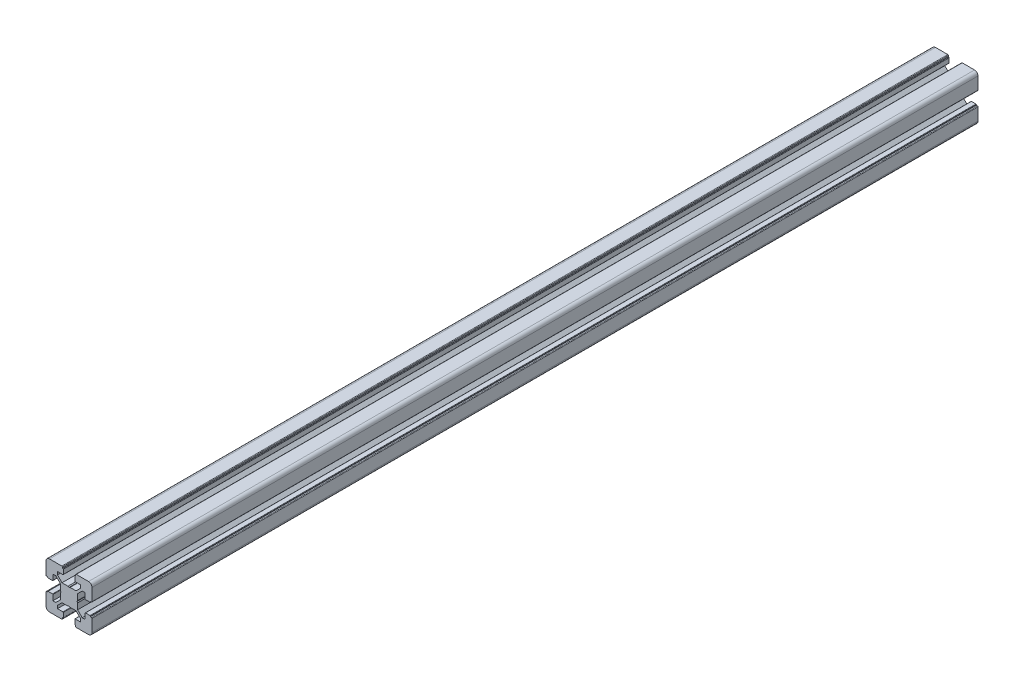
SolidWorks part; units mm, degrees
material "1060 Alloy"
ref_plane "Front Plane" through (0, 0, 0) normal (0, 0, 1) x (1, 0, 0)
ref_plane "Top Plane" through (0, 0, 0) normal (0, 1, 0) x (1, 0, 0)
ref_plane "Right Plane" through (0, 0, 0) normal (1, 0, 0) x (0, 0, -1)
sketch "Sketch2" plane through (0, 0, 0) normal (0, 0, 1) x (1, 0, 0)
  line L72 (-20.3, 9.9499) -> (-20.3, 14.7)
  line L73 (-20.6, 15) -> (-24.5, 15)
  line L74 (-24.8, 14.7) -> (-24.8, 14.2)
  line L75 (-24.8, 14.2) -> (-25.8, 14.2)
  line L76 (-26.3, 13.7) -> (-26.3, 3)
  line L77 (-23.3, 0) -> (-12.6, 0)
  line L78 (-12.1, 0.5) -> (-12.1, 1.5)
  line L79 (-12.1, 1.5) -> (-11.6, 1.5)
  line L80 (-11.3, 1.8) -> (-11.3, 5.7)
  line L81 (-11.6, 6) -> (-16.3501, 6)
  line L82 (-16.3501, 6) -> (-16.3501, 8.5356)
  line L83 (-16.3501, 8.5356) -> (-12.3856, 12.5001)
  line L84 (-12.3856, 12.5001) -> (-7.166, 12.5001)
  line L85 (-7.166, 12.5001) -> (-6.3, 13.0001)
  line L86 (-6.3, 13.0001) -> (-5.4339, 12.5001)
  line L87 (-5.4339, 12.5001) -> (-0.2143, 12.5001)
  line L88 (-0.2143, 12.5001) -> (3.7501, 8.5357)
  line L89 (3.7501, 8.5357) -> (3.7501, 6)
  line L90 (3.7501, 6) -> (-1, 6)
  line L91 (-1.3, 5.7) -> (-1.3, 1.8)
  line L92 (-1, 1.5) -> (-0.5, 1.5)
  line L93 (-0.5, 1.5) -> (-0.5, 0.5)
  line L94 (0, 0) -> (10.7, 0)
  line L95 (13.7, 3) -> (13.7, 13.7)
  line L96 (13.2, 14.2) -> (12.2, 14.2)
  line L97 (12.2, 14.2) -> (12.2, 14.7)
  line L98 (11.9, 15) -> (8, 15)
  line L99 (7.7, 14.7) -> (7.7, 9.9498)
  line L100 (7.7, 9.9498) -> (5.1644, 9.9498)
  line L101 (5.1644, 9.9498) -> (1.1999, 13.9143)
  line L102 (1.1999, 13.9143) -> (1.1999, 19.134)
  line L103 (1.1999, 19.134) -> (0.6999, 20)
  line L104 (0.6999, 20) -> (1.1999, 20.866)
  line L105 (1.1999, 20.866) -> (1.1999, 26.0857)
  line L106 (1.1999, 26.0857) -> (5.1643, 30.0501)
  line L107 (5.1643, 30.0501) -> (7.7, 30.0501)
  line L108 (7.7, 30.0501) -> (7.7, 25.3)
  line L109 (8, 25) -> (11.9, 25)
  line L110 (12.2, 25.3) -> (12.2, 25.8)
  line L111 (12.2, 25.8) -> (13.2, 25.8)
  line L112 (13.7, 26.3) -> (13.7, 37)
  line L113 (10.7, 40) -> (0.0001, 40)
  line L114 (-0.4999, 39.5) -> (-0.4999, 38.5)
  line L115 (-0.4999, 38.5) -> (-0.9999, 38.5)
  line L116 (-1.2999, 38.2) -> (-1.2999, 34.3)
  line L117 (-0.9999, 34) -> (3.7502, 34)
  line L118 (3.7502, 34) -> (3.7502, 31.4644)
  line L119 (3.7502, 31.4644) -> (-0.2143, 27.4999)
  line L120 (-0.2143, 27.4999) -> (-5.4339, 27.4999)
  line L121 (-5.4339, 27.4999) -> (-6.3, 26.9999)
  line L122 (-6.3, 26.9999) -> (-7.166, 27.4999)
  line L123 (-7.166, 27.4999) -> (-12.3856, 27.4999)
  line L124 (-12.3856, 27.4999) -> (-16.3501, 31.4643)
  line L125 (-16.3501, 31.4643) -> (-16.3501, 34)
  line L126 (-16.3501, 34) -> (-11.5999, 34)
  line L127 (-11.2999, 34.3) -> (-11.2999, 38.2)
  line L128 (-11.5999, 38.5) -> (-12.0999, 38.5)
  line L129 (-12.0999, 38.5) -> (-12.0999, 39.5)
  line L130 (-12.5999, 40) -> (-23.3, 40)
  line L131 (-26.3, 37) -> (-26.3, 26.3)
  line L132 (-25.8, 25.8) -> (-24.8, 25.8)
  line L133 (-24.8, 25.8) -> (-24.8, 25.3)
  line L134 (-24.5, 25) -> (-20.6, 25)
  line L135 (-20.3, 25.3) -> (-20.3, 30.0502)
  line L136 (-20.3, 30.0502) -> (-17.7643, 30.0502)
  line L137 (-17.7643, 30.0502) -> (-13.7999, 26.0857)
  line L138 (-13.7999, 26.0857) -> (-13.7999, 20.866)
  line L139 (-13.7999, 20.866) -> (-13.2999, 20)
  line L140 (-13.2999, 20) -> (-13.7999, 19.134)
  line L141 (-13.7999, 19.134) -> (-13.7999, 13.9143)
  line L142 (-13.7999, 13.9143) -> (-17.7643, 9.9499)
  line L143 (-17.7643, 9.9499) -> (-20.3, 9.9499)
  line L144 (-20.3, 9.9499) -> (-20.3, 14.7)
  line L145 (-20.6, 15) -> (-24.5, 15)
  line L146 (-24.8, 14.7) -> (-24.8, 14.2)
  line L147 (-24.8, 14.2) -> (-25.8, 14.2)
  line L148 (-26.3, 13.7) -> (-26.3, 3)
  line L149 (-23.3, 0) -> (-12.6, 0)
  line L150 (-12.1, 0.5) -> (-12.1, 1.5)
  line L151 (-12.1, 1.5) -> (-11.6, 1.5)
  line L152 (-11.3, 1.8) -> (-11.3, 5.7)
  line L153 (-11.6, 6) -> (-16.3501, 6)
  line L154 (-16.3501, 6) -> (-16.3501, 8.5356)
  line L155 (-16.3501, 8.5356) -> (-12.3856, 12.5001)
  line L156 (-12.3856, 12.5001) -> (-7.166, 12.5001)
  line L157 (-7.166, 12.5001) -> (-6.3, 13.0001)
  line L158 (-6.3, 13.0001) -> (-5.4339, 12.5001)
  line L159 (-5.4339, 12.5001) -> (-0.2143, 12.5001)
  line L160 (-0.2143, 12.5001) -> (3.7501, 8.5357)
  line L161 (3.7501, 8.5357) -> (3.7501, 6)
  line L162 (3.7501, 6) -> (-1, 6)
  line L163 (-1.3, 5.7) -> (-1.3, 1.8)
  line L164 (-1, 1.5) -> (-0.5, 1.5)
  line L165 (-0.5, 1.5) -> (-0.5, 0.5)
  line L166 (0, 0) -> (10.7, 0)
  line L167 (13.7, 3) -> (13.7, 13.7)
  line L168 (13.2, 14.2) -> (12.2, 14.2)
  line L169 (12.2, 14.2) -> (12.2, 14.7)
  line L170 (11.9, 15) -> (8, 15)
  line L171 (7.7, 14.7) -> (7.7, 9.9498)
  line L172 (7.7, 9.9498) -> (5.1644, 9.9498)
  line L173 (5.1644, 9.9498) -> (1.1999, 13.9143)
  line L174 (1.1999, 13.9143) -> (1.1999, 19.134)
  line L175 (1.1999, 19.134) -> (0.6999, 20)
  line L176 (0.6999, 20) -> (1.1999, 20.866)
  line L177 (1.1999, 20.866) -> (1.1999, 26.0857)
  line L178 (1.1999, 26.0857) -> (5.1643, 30.0501)
  line L179 (5.1643, 30.0501) -> (7.7, 30.0501)
  line L180 (7.7, 30.0501) -> (7.7, 25.3)
  line L181 (8, 25) -> (11.9, 25)
  line L182 (12.2, 25.3) -> (12.2, 25.8)
  line L183 (12.2, 25.8) -> (13.2, 25.8)
  line L184 (13.7, 26.3) -> (13.7, 37)
  line L185 (10.7, 40) -> (0.0001, 40)
  line L186 (-0.4999, 39.5) -> (-0.4999, 38.5)
  line L187 (-0.4999, 38.5) -> (-0.9999, 38.5)
  line L188 (-1.2999, 38.2) -> (-1.2999, 34.3)
  line L189 (-0.9999, 34) -> (3.7502, 34)
  line L190 (3.7502, 34) -> (3.7502, 31.4644)
  line L191 (3.7502, 31.4644) -> (-0.2143, 27.4999)
  line L192 (-0.2143, 27.4999) -> (-5.4339, 27.4999)
  line L193 (-5.4339, 27.4999) -> (-6.3, 26.9999)
  line L194 (-6.3, 26.9999) -> (-7.166, 27.4999)
  line L195 (-7.166, 27.4999) -> (-12.3856, 27.4999)
  line L196 (-12.3856, 27.4999) -> (-16.3501, 31.4643)
  line L197 (-16.3501, 31.4643) -> (-16.3501, 34)
  line L198 (-16.3501, 34) -> (-11.5999, 34)
  line L199 (-11.2999, 34.3) -> (-11.2999, 38.2)
  line L200 (-11.5999, 38.5) -> (-12.0999, 38.5)
  line L201 (-12.0999, 38.5) -> (-12.0999, 39.5)
  line L202 (-12.5999, 40) -> (-23.3, 40)
  line L203 (-26.3, 37) -> (-26.3, 26.3)
  line L204 (-25.8, 25.8) -> (-24.8, 25.8)
  line L205 (-24.8, 25.8) -> (-24.8, 25.3)
  line L206 (-24.5, 25) -> (-20.6, 25)
  line L207 (-20.3, 25.3) -> (-20.3, 30.0502)
  line L208 (-20.3, 30.0502) -> (-17.7643, 30.0502)
  line L209 (-17.7643, 30.0502) -> (-13.7999, 26.0857)
  line L210 (-13.7999, 26.0857) -> (-13.7999, 20.866)
  line L211 (-13.7999, 20.866) -> (-13.2999, 20)
  line L212 (-13.2999, 20) -> (-13.7999, 19.134)
  line L213 (-13.7999, 19.134) -> (-13.7999, 13.9143)
  line L214 (-13.7999, 13.9143) -> (-17.7643, 9.9499)
  line L215 (-17.7643, 9.9499) -> (-20.3, 9.9499)
  arc A28 (-20.3, 14.7) -> (-20.6, 15) centre (-20.6, 14.7) ccw
  arc A29 (-24.5, 15) -> (-24.8, 14.7) centre (-24.5, 14.7) ccw
  arc A30 (-25.8, 14.2) -> (-26.3, 13.7) centre (-25.8, 13.7) ccw
  arc A31 (-26.3, 3) -> (-23.3, 0) centre (-23.3, 3) ccw
  arc A32 (-12.6, 0) -> (-12.1, 0.5) centre (-12.6, 0.5) ccw
  arc A33 (-11.6, 1.5) -> (-11.3, 1.8) centre (-11.6, 1.8) ccw
  arc A34 (-11.3, 5.7) -> (-11.6, 6) centre (-11.6, 5.7) ccw
  arc A35 (-1, 6) -> (-1.3, 5.7) centre (-1, 5.7) ccw
  arc A36 (-1.3, 1.8) -> (-1, 1.5) centre (-1, 1.8) ccw
  arc A37 (-0.5, 0.5) -> (0, 0) centre (0, 0.5) ccw
  arc A38 (10.7, 0) -> (13.7, 3) centre (10.7, 3) ccw
  arc A39 (13.7, 13.7) -> (13.2, 14.2) centre (13.2, 13.7) ccw
  arc A40 (12.2, 14.7) -> (11.9, 15) centre (11.9, 14.7) ccw
  arc A41 (8, 15) -> (7.7, 14.7) centre (8, 14.7) ccw
  arc A42 (7.7, 25.3) -> (8, 25) centre (8, 25.3) ccw
  arc A43 (11.9, 25) -> (12.2, 25.3) centre (11.9, 25.3) ccw
  arc A44 (13.2, 25.8) -> (13.7, 26.3) centre (13.2, 26.3) ccw
  arc A45 (13.7, 37) -> (10.7, 40) centre (10.7, 37) ccw
  arc A46 (0.0001, 40) -> (-0.4999, 39.5) centre (0.0001, 39.5) ccw
  arc A47 (-0.9999, 38.5) -> (-1.2999, 38.2) centre (-0.9999, 38.2) ccw
  arc A48 (-1.2999, 34.3) -> (-0.9999, 34) centre (-0.9999, 34.3) ccw
  arc A49 (-11.5999, 34) -> (-11.2999, 34.3) centre (-11.5999, 34.3) ccw
  arc A50 (-11.2999, 38.2) -> (-11.5999, 38.5) centre (-11.5999, 38.2) ccw
  arc A51 (-12.0999, 39.5) -> (-12.5999, 40) centre (-12.5999, 39.5) ccw
  arc A52 (-23.3, 40) -> (-26.3, 37) centre (-23.3, 37) ccw
  arc A53 (-26.3, 26.3) -> (-25.8, 25.8) centre (-25.8, 26.3) ccw
  arc A54 (-24.8, 25.3) -> (-24.5, 25) centre (-24.5, 25.3) ccw
  arc A55 (-20.6, 25) -> (-20.3, 25.3) centre (-20.6, 25.3) ccw
  arc A56 (-20.3, 14.7) -> (-20.6, 15) centre (-20.6, 14.7) ccw
  arc A57 (-24.5, 15) -> (-24.8, 14.7) centre (-24.5, 14.7) ccw
  arc A58 (-25.8, 14.2) -> (-26.3, 13.7) centre (-25.8, 13.7) ccw
  arc A59 (-26.3, 3) -> (-23.3, 0) centre (-23.3, 3) ccw
  arc A60 (-12.6, 0) -> (-12.1, 0.5) centre (-12.6, 0.5) ccw
  arc A61 (-11.6, 1.5) -> (-11.3, 1.8) centre (-11.6, 1.8) ccw
  arc A62 (-11.3, 5.7) -> (-11.6, 6) centre (-11.6, 5.7) ccw
  arc A63 (-1, 6) -> (-1.3, 5.7) centre (-1, 5.7) ccw
  arc A64 (-1.3, 1.8) -> (-1, 1.5) centre (-1, 1.8) ccw
  arc A65 (-0.5, 0.5) -> (0, 0) centre (0, 0.5) ccw
  arc A66 (10.7, 0) -> (13.7, 3) centre (10.7, 3) ccw
  arc A67 (13.7, 13.7) -> (13.2, 14.2) centre (13.2, 13.7) ccw
  arc A68 (12.2, 14.7) -> (11.9, 15) centre (11.9, 14.7) ccw
  arc A69 (8, 15) -> (7.7, 14.7) centre (8, 14.7) ccw
  arc A70 (7.7, 25.3) -> (8, 25) centre (8, 25.3) ccw
  arc A71 (11.9, 25) -> (12.2, 25.3) centre (11.9, 25.3) ccw
  arc A72 (13.2, 25.8) -> (13.7, 26.3) centre (13.2, 26.3) ccw
  arc A73 (13.7, 37) -> (10.7, 40) centre (10.7, 37) ccw
  arc A74 (0.0001, 40) -> (-0.4999, 39.5) centre (0.0001, 39.5) ccw
  arc A75 (-0.9999, 38.5) -> (-1.2999, 38.2) centre (-0.9999, 38.2) ccw
  arc A76 (-1.2999, 34.3) -> (-0.9999, 34) centre (-0.9999, 34.3) ccw
  arc A77 (-11.5999, 34) -> (-11.2999, 34.3) centre (-11.5999, 34.3) ccw
  arc A78 (-11.2999, 38.2) -> (-11.5999, 38.5) centre (-11.5999, 38.2) ccw
  arc A79 (-12.0999, 39.5) -> (-12.5999, 40) centre (-12.5999, 39.5) ccw
  arc A80 (-23.3, 40) -> (-26.3, 37) centre (-23.3, 37) ccw
  arc A81 (-26.3, 26.3) -> (-25.8, 25.8) centre (-25.8, 26.3) ccw
  arc A82 (-24.8, 25.3) -> (-24.5, 25) centre (-24.5, 25.3) ccw
  arc A83 (-20.6, 25) -> (-20.3, 25.3) centre (-20.6, 25.3) ccw
  dimension "D1" = 0
extrude "Boss-Extrude1" add sketch "Sketch2" along normal blind 770 contours L202 A80 L203 A81 L204 L205 A82 L206 A83 L207 L208 L209 L210 L211 L212 L213 L214 L215 L144 A56 L145 A57 L146 L147 A58 L148 A59 L149 A60 L150 L151 A61 L152 A62 L153 L154 L155 L156 L157 L158 L159 L160 L161 L162 A63 L163 A64 L164 L165 A65 L166 A66 L167 A67 L168 L169 A68 L170 A69 L171 L172 L173 L174 L175 L176 L177 L178 L179 L180 A70 L181 A71 L182 L183 A72 L184 A73 L185 A74 L186 L187 A75 L188 A76 L189 L190 L191 L192 L193 L194 L195 L196 L197 L198 A77 L199 A78 L200 L201 A79
